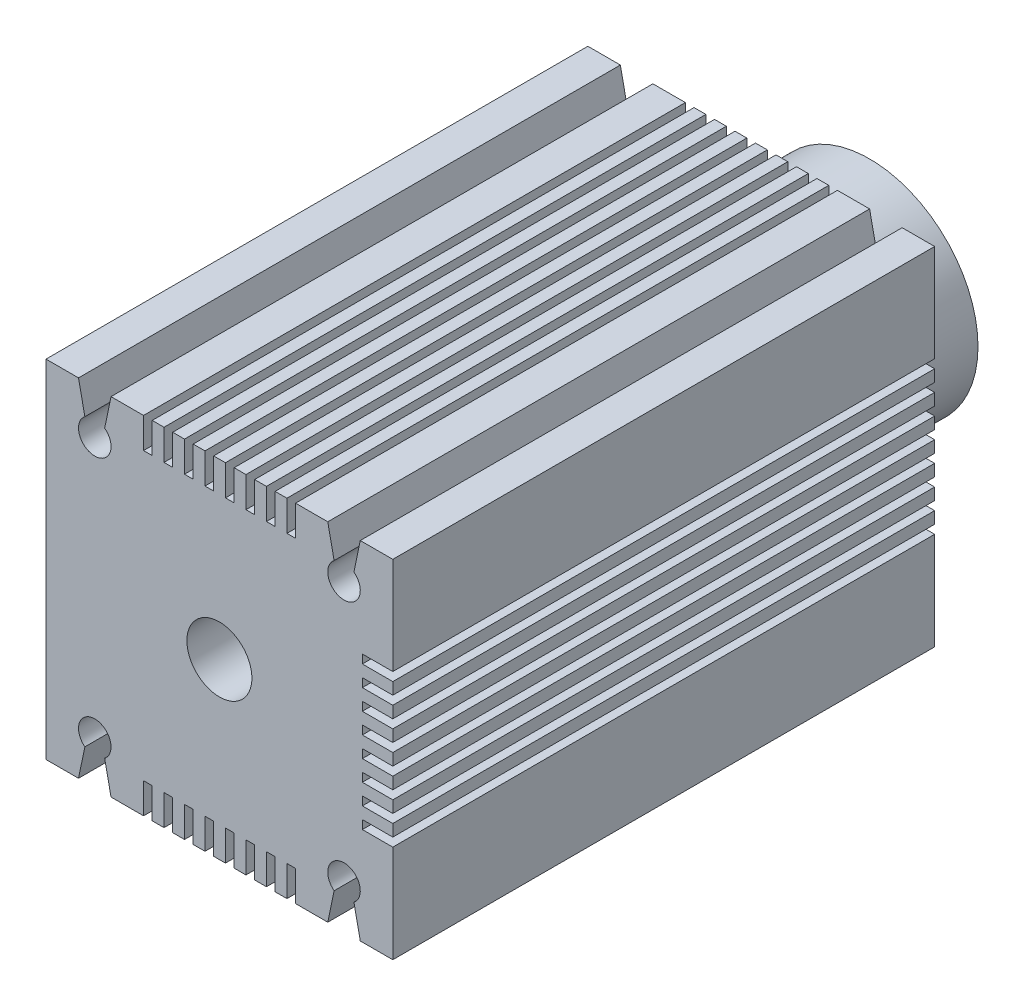
SolidWorks part; units mm, degrees
ref_plane "Спереди" through (0, 0, 0) normal (0, 0, 1) x (1, 0, 0)
ref_plane "Сверху" through (0, 0, 0) normal (0, 1, 0) x (1, 0, 0)
ref_plane "Справа" through (0, 0, 0) normal (1, 0, 0) x (0, 0, -1)
sketch "Эскиз1" plane through (0, 0, 0) normal (0, 0, 1) x (1, 0, 0)
  line L1 (-16, 16) -> (16, 16)
  line L2 (-16, 16) -> (-16, -16)
  line L3 (-16, -16) -> (16, -16)
  line L4 (16, 16) -> (16, -16)
  line L5 (-16, 16) -> (16, -16) construction
  line L6 (-16, -16) -> (16, 16) construction
  point P0 (0, 0)
  dimension "D1" = 32
  dimension "D2" = 32
extrude "Бобышка-Вытянуть2" add sketch "Эскиз1" along normal blind 50
sketch "Эскиз3" plane through (0, 0, 50) normal (0, 0, 1) x (1, 0, 0)
  line L0 (-16, 16) -> (-13, 16)
  line L1 (16, 16) -> (-16, 16) construction
  line L2 (-13, 16) -> (-12.4135, 13.1898)
  line L3 (10, 16) -> (10.5865, 13.1898)
  line L4 (10, 16) -> (7, 16)
  line L5 (-10, 16) -> (-7, 16)
  line L6 (0, 16) -> (0, -16)
  line L7 (-16, -16) -> (16, -16) construction
  line L8 (-10, 16) -> (-10.5865, 13.1898)
  line L9 (13, 16) -> (12.4135, 13.1898)
  line L10 (16, 16) -> (13, 16)
  line L11 (-7, 16) -> (-7, 13.1898)
  line L12 (-7, 13.1898) -> (-6.2, 13.1898)
  line L13 (-6.2, 13.1898) -> (-6.2, 16)
  line L14 (-6.2, 16) -> (-7, 16)
  line L15 (-5.11, 16) -> (-5.11, 13.1898)
  line L16 (-4.31, 16) -> (-5.11, 16)
  line L17 (-4.31, 13.1898) -> (-4.31, 16)
  line L18 (-5.11, 13.1898) -> (-4.31, 13.1898)
  line L19 (-3.22, 16) -> (-3.22, 13.1898)
  line L20 (-2.42, 16) -> (-3.22, 16)
  line L21 (-2.42, 13.1898) -> (-2.42, 16)
  line L22 (-3.22, 13.1898) -> (-2.42, 13.1898)
  line L23 (-1.33, 16) -> (-1.33, 13.1898)
  line L24 (-0.53, 16) -> (-1.33, 16)
  line L25 (-0.53, 13.1898) -> (-0.53, 16)
  line L26 (-1.33, 13.1898) -> (-0.53, 13.1898)
  line L27 (0.56, 16) -> (0.56, 13.1898)
  line L28 (1.36, 16) -> (0.56, 16)
  line L29 (1.36, 13.1898) -> (1.36, 16)
  line L30 (0.56, 13.1898) -> (1.36, 13.1898)
  line L31 (2.45, 16) -> (2.45, 13.1898)
  line L32 (3.25, 16) -> (2.45, 16)
  line L33 (3.25, 13.1898) -> (3.25, 16)
  line L34 (2.45, 13.1898) -> (3.25, 13.1898)
  line L35 (4.34, 16) -> (4.34, 13.1898)
  line L36 (5.14, 16) -> (4.34, 16)
  line L37 (5.14, 13.1898) -> (5.14, 16)
  line L38 (4.34, 13.1898) -> (5.14, 13.1898)
  line L39 (6.23, 16) -> (6.23, 13.1898)
  line L40 (7.03, 16) -> (6.23, 16)
  line L41 (7.03, 13.1898) -> (7.03, 16)
  line L42 (6.23, 13.1898) -> (7.03, 13.1898)
  line L43 (0, 0) -> (16, 0)
  line L44 (16, -16) -> (16, 16) construction
  line L45 (6.23, -13.1898) -> (7.03, -13.1898)
  line L46 (7.03, -13.1898) -> (7.03, -16)
  line L47 (7.03, -16) -> (6.23, -16)
  line L48 (6.23, -16) -> (6.23, -13.1898)
  line L49 (4.34, -13.1898) -> (5.14, -13.1898)
  line L50 (5.14, -13.1898) -> (5.14, -16)
  line L51 (5.14, -16) -> (4.34, -16)
  line L52 (4.34, -16) -> (4.34, -13.1898)
  line L53 (2.45, -13.1898) -> (3.25, -13.1898)
  line L54 (3.25, -13.1898) -> (3.25, -16)
  line L55 (3.25, -16) -> (2.45, -16)
  line L56 (2.45, -16) -> (2.45, -13.1898)
  line L57 (0.56, -13.1898) -> (1.36, -13.1898)
  line L58 (1.36, -13.1898) -> (1.36, -16)
  line L59 (1.36, -16) -> (0.56, -16)
  line L60 (0.56, -16) -> (0.56, -13.1898)
  line L61 (-1.33, -13.1898) -> (-0.53, -13.1898)
  line L62 (-0.53, -13.1898) -> (-0.53, -16)
  line L63 (-0.53, -16) -> (-1.33, -16)
  line L64 (-1.33, -16) -> (-1.33, -13.1898)
  line L65 (-3.22, -13.1898) -> (-2.42, -13.1898)
  line L66 (-2.42, -13.1898) -> (-2.42, -16)
  line L67 (-2.42, -16) -> (-3.22, -16)
  line L68 (-3.22, -16) -> (-3.22, -13.1898)
  line L69 (-5.11, -13.1898) -> (-4.31, -13.1898)
  line L70 (-4.31, -13.1898) -> (-4.31, -16)
  line L71 (-4.31, -16) -> (-5.11, -16)
  line L72 (-5.11, -16) -> (-5.11, -13.1898)
  line L73 (-6.2, -16) -> (-7, -16)
  line L74 (-6.2, -13.1898) -> (-6.2, -16)
  line L75 (-7, -13.1898) -> (-6.2, -13.1898)
  line L76 (-7, -16) -> (-7, -13.1898)
  line L77 (16, -16) -> (13, -16)
  line L78 (13, -16) -> (12.4135, -13.1898)
  line L79 (-10, -16) -> (-10.5865, -13.1898)
  line L80 (-10, -16) -> (-7, -16)
  line L81 (10, -16) -> (7, -16)
  line L82 (10, -16) -> (10.5865, -13.1898)
  line L83 (-13, -16) -> (-12.4135, -13.1898)
  line L84 (-16, -16) -> (-13, -16)
  line L85 (-16, -16) -> (-16, -7)
  line L86 (-16, 16) -> (-16, -16) construction
  line L87 (-16, -7) -> (-13.19, -7)
  line L88 (-13.19, -7) -> (-13.19, -6.2)
  line L89 (-13.19, -6.2) -> (-16, -6.2)
  line L90 (-16, -6.2) -> (-16, -7)
  line L91 (-13.19, -4.31) -> (-16, -4.31)
  line L92 (-13.19, -5.11) -> (-13.19, -4.31)
  line L93 (-16, -5.11) -> (-13.19, -5.11)
  line L94 (-16, -4.31) -> (-16, -5.11)
  line L95 (-13.19, -2.42) -> (-16, -2.42)
  line L96 (-13.19, -3.22) -> (-13.19, -2.42)
  line L97 (-16, -3.22) -> (-13.19, -3.22)
  line L98 (-16, -2.42) -> (-16, -3.22)
  line L99 (-13.19, -0.53) -> (-16, -0.53)
  line L100 (-13.19, -1.33) -> (-13.19, -0.53)
  line L101 (-16, -1.33) -> (-13.19, -1.33)
  line L102 (-16, -0.53) -> (-16, -1.33)
  line L103 (-13.19, 1.36) -> (-16, 1.36)
  line L104 (-13.19, 0.56) -> (-13.19, 1.36)
  line L105 (-16, 0.56) -> (-13.19, 0.56)
  line L106 (-16, 1.36) -> (-16, 0.56)
  line L107 (-13.19, 3.25) -> (-16, 3.25)
  line L108 (-13.19, 2.45) -> (-13.19, 3.25)
  line L109 (-16, 2.45) -> (-13.19, 2.45)
  line L110 (-16, 3.25) -> (-16, 2.45)
  line L111 (-13.19, 5.14) -> (-16, 5.14)
  line L112 (-13.19, 4.34) -> (-13.19, 5.14)
  line L113 (-16, 4.34) -> (-13.19, 4.34)
  line L114 (-16, 5.14) -> (-16, 4.34)
  line L115 (-13.19, 7.03) -> (-16, 7.03)
  line L116 (-13.19, 6.23) -> (-13.19, 7.03)
  line L117 (-16, 6.23) -> (-13.19, 6.23)
  line L118 (-16, 7.03) -> (-16, 6.23)
  line L119 (16, 7.03) -> (16, 6.23)
  line L120 (16, 6.23) -> (13.19, 6.23)
  line L121 (13.19, 6.23) -> (13.19, 7.03)
  line L122 (13.19, 7.03) -> (16, 7.03)
  line L123 (16, 5.14) -> (16, 4.34)
  line L124 (16, 4.34) -> (13.19, 4.34)
  line L125 (13.19, 4.34) -> (13.19, 5.14)
  line L126 (13.19, 5.14) -> (16, 5.14)
  line L127 (16, 3.25) -> (16, 2.45)
  line L128 (16, 2.45) -> (13.19, 2.45)
  line L129 (13.19, 2.45) -> (13.19, 3.25)
  line L130 (13.19, 3.25) -> (16, 3.25)
  line L131 (16, 1.36) -> (16, 0.56)
  line L132 (16, 0.56) -> (13.19, 0.56)
  line L133 (13.19, 0.56) -> (13.19, 1.36)
  line L134 (13.19, 1.36) -> (16, 1.36)
  line L135 (16, -0.53) -> (16, -1.33)
  line L136 (16, -1.33) -> (13.19, -1.33)
  line L137 (13.19, -1.33) -> (13.19, -0.53)
  line L138 (13.19, -0.53) -> (16, -0.53)
  line L139 (16, -2.42) -> (16, -3.22)
  line L140 (16, -3.22) -> (13.19, -3.22)
  line L141 (13.19, -3.22) -> (13.19, -2.42)
  line L142 (13.19, -2.42) -> (16, -2.42)
  line L143 (16, -4.31) -> (16, -5.11)
  line L144 (16, -5.11) -> (13.19, -5.11)
  line L145 (13.19, -5.11) -> (13.19, -4.31)
  line L146 (13.19, -4.31) -> (16, -4.31)
  line L147 (16, -6.2) -> (16, -7)
  line L148 (16, -7) -> (13.19, -7)
  line L149 (13.19, -7) -> (13.19, -6.2)
  line L150 (13.19, -6.2) -> (16, -6.2)
  line L151 (-13, 16) -> (13, 16)
  line L152 (-13, -16) -> (13, -16)
  arc A0 (-12.4135, 13.1898) -> (-10.5865, 13.1898) centre (-11.5, 12) ccw
  arc A1 (12.4135, 13.1898) -> (10.5865, 13.1898) centre (11.5, 12) cw
  arc A2 (12.4135, -13.1898) -> (10.5865, -13.1898) centre (11.5, -12) ccw
  arc A3 (-12.4135, -13.1898) -> (-10.5865, -13.1898) centre (-11.5, -12) cw
  line M46 (16, -16) -> (16, 16)
  line M47 (16, 16) -> (-16, 16)
  line M48 (-16, 16) -> (-16, -16)
  line M49 (-16, -16) -> (16, -16)
  dimension "D1" = 3
  dimension "D2" = 0.8
  dimension "D3" = 3
  dimension "D4" = 8
  dimension "D5" = 9
  dimension "D6" = 2.81
  dimension "D7" = 0.8
  dimension "D8" = 8
extrude "Вырез-Вытянуть1" cut sketch "Эскиз3" against normal through all contours L2 A0 L8 M47 | L12 L13 L11 M47 | L15 L18 L17 M47 | L19 L22 L21 M47 | L23 L26 L25 M47 | L27 L30 L29 M47 | L31 L34 L33 M47 | L35 L38 L37 M47 | L39 L42 L41 L4 M47 | A1 L9 L3 M47 | L117 L116 L115 M48 | L113 L112 L111 M48 | L109 L108 L107 M48 | L105 L104 L103 M48 | L101 L100 L99 M48 | L97 L96 L95 M48 | L88 L89 L87 M48 | L93 L92 L91 M48 | A3 L83 L79 M49 | L76 L74 L75 M49 | L72 L70 L69 M49 | L68 L66 L65 M49 | L64 L62 L61 M49 | L60 L58 L57 M49 | L56 L54 L53 M49 | L52 L50 L49 M49 | L48 L47 L46 L45 M49 | L78 A2 L82 M49 | L150 L149 L148 M46 | L146 L145 L144 M46 | L142 L141 L140 M46 | L138 L137 L136 M46 | L134 L133 L132 M46 | L130 L129 L128 M46 | L122 L121 L120 M46 | L126 L123 L124 L125
sketch "Эскиз4" plane through (0, 0, 0) normal (0, 0, -1) x (-1, 0, 0)
  circle A0 centre (0, 0) radius 10
  dimension "D1" = 20
extrude "Бобышка-Вытянуть3" add sketch "Эскиз4" along normal blind 10
sketch "Эскиз5" plane through (0, 0, -10) normal (0, 0, -1) x (-1, 0, 0)
  circle A0 centre (0, 0) radius 3
  dimension "D1" = 6
extrude "Вырез-Вытянуть2" cut sketch "Эскиз5" against normal through all
sketch "Эскиз6" plane through (0, 0, 50) normal (0, 0, 1) x (1, 0, 0)
  line L1 (-13.19, 7.03) -> (-16, 7.03)
  line L2 (-13.19, 7.03) -> (-13.19, -7)
  line L3 (-13.19, -7) -> (-16, -7)
  line L4 (-16, 7.03) -> (-16, -7)
extrude "Бобышка-Вытянуть4" add sketch "Эскиз6" against normal blind 50
sketch "Эскиз7" plane through (-16, 0, 0) normal (-1, 0, 0) x (0, 0, 1)
  line L0 (0, 16) -> (0, 8)
  line L1 (0, 16) -> (0, -16) construction
  line L2 (0, 8) -> (4.5, 8)
  line L3 (0, 0) -> (4.5, 0)
  line L4 (0, -8) -> (4.5, -8)
  line L5 (0, -16) -> (0, -8)
  line L6 (25, 16) -> (25, -16)
  line L7 (50, 16) -> (0, 16) construction
  line L8 (50, -16) -> (0, -16) construction
  circle A0 centre (4.5, 8) radius 1.5
  circle A1 centre (4.5, -8) radius 1.5
  circle A2 centre (4.5, 0) radius 1.5
  circle A3 centre (45.5, 0) radius 1.5
  circle A4 centre (45.5, -8) radius 1.5
  circle A5 centre (45.5, 8) radius 1.5
  circle A6 centre (25, 0) radius 2.5
  dimension "D3" = 3
  dimension "D5" = 5
  dimension "D1" = 8
  dimension "D2" = 4.5
  dimension "D4" = 4.5
extrude "Вырез-Вытянуть3" cut sketch "Эскиз7" against normal blind 10
fillet "Скругление1" radius 1 7 edges at (-16, -9.5, 45.5) (-16, -1.5, 45.5) (-16, 6.5, 45.5) (-16, -2.5, 25) (-16, -9.5, 4.5) (-16, -1.5, 4.5) (-16, 6.5, 4.5)
